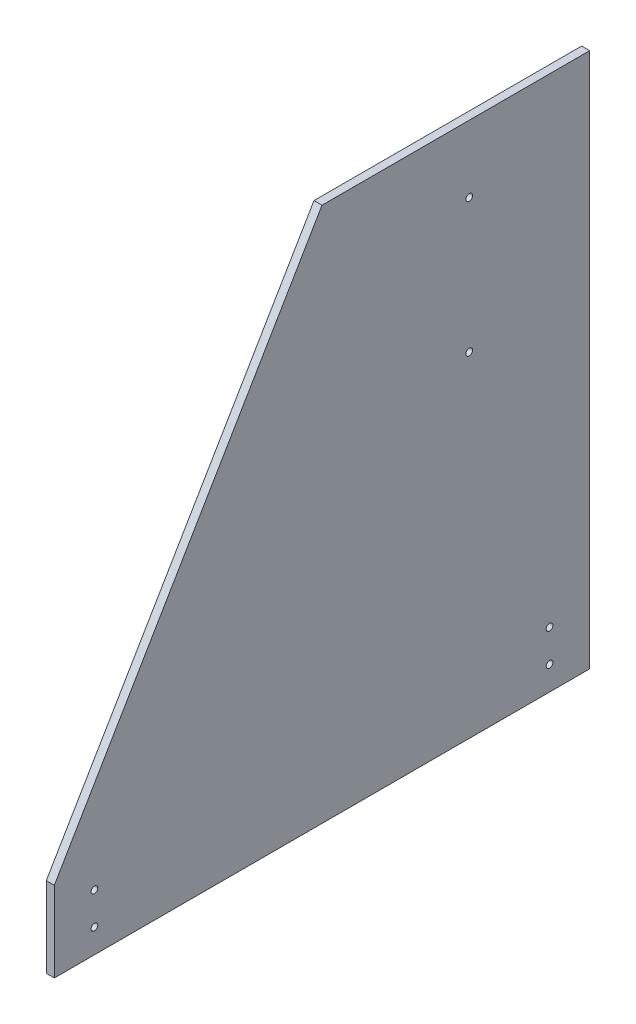
SolidWorks part; units mm, degrees
ref_plane "Front Plane" through (0, 0, 0) normal (0, 0, 1) x (1, 0, 0)
ref_plane "Top Plane" through (0, 0, 0) normal (0, 1, 0) x (1, 0, 0)
ref_plane "Right Plane" through (0, 0, 0) normal (1, 0, 0) x (0, 0, -1)
sketch "Sketch1" plane through (0, 0, 0) normal (1, 0, 0) x (0, 0, -1)
  line L0 (0, -2343.7616) -> (0, 114844.3172) construction
  line L1 (-2343.7616, 0) -> (114844.3172, 0) construction
  line L2 (0, 60) -> (400, 60) construction
  line L3 (0, 0) -> (400, 0)
  line L5 (200, 400) -> (400, 400)
  line L6 (400, 0) -> (400, 400)
  line L7 (0, 60) -> (200, 400)
  line L8 (0, 60) -> (0, 0)
  line L9 (-1000, 30) -> (49000, 30) construction
  line L10 (200, -1000) -> (200, 49000) construction
  line L11 (310, -1000) -> (310, 49000) construction
  circle A0 centre (30, 42) radius 2.5
  circle A2 centre (30, 18) radius 2.5
  circle A3 centre (370, 18) radius 2.5
  circle A4 centre (370, 42) radius 2.5
  circle A5 centre (310, 350) radius 2.5
  circle A6 centre (310, 250) radius 2.5
  point P14 (0, 30)
  point P21 (200, 0)
  dimension "D7" = 5
  dimension "D9" = 5
  dimension "D1" = 400
  dimension "D2" = 400
  dimension "D3" = 60
  dimension "D4" = 200
  dimension "D5" = 30
  dimension "D6" = 90
  dimension "D8" = 12
  dimension "D10" = 50
  dimension "D11" = 100
extrude "Boss-Extrude1" add sketch "Sketch1" along normal blind 6
